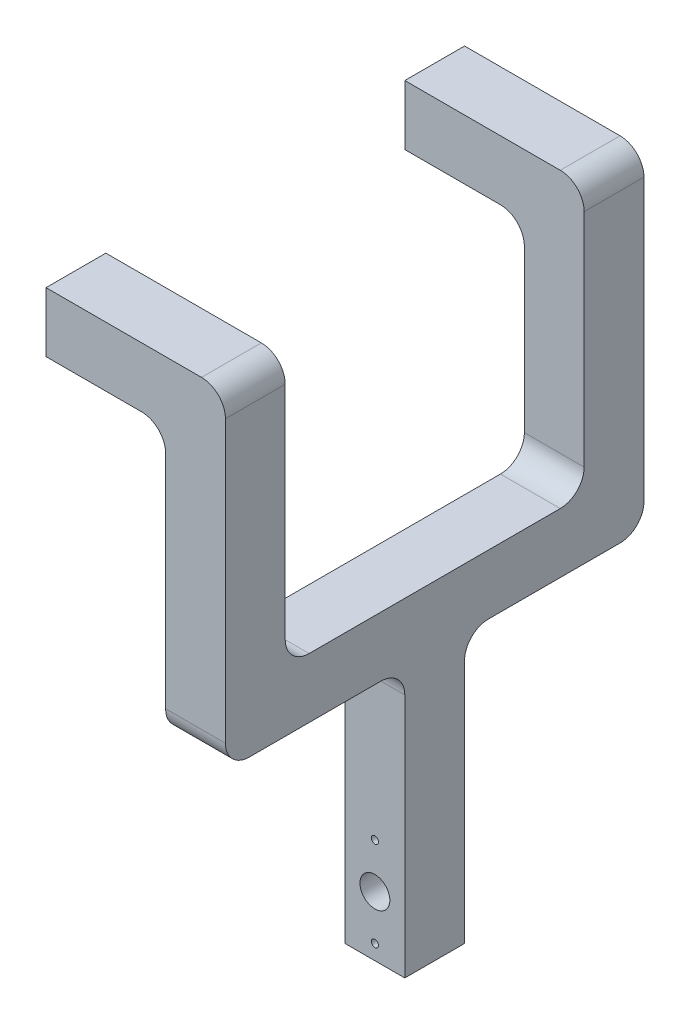
SolidWorks part; units mm, degrees
other "Marquage1"
sketch "Esquisse8" plane through (14, 100, 40) normal (0.0145, 0.0452, 0.9989) x (0.9993, 0.0332, -0.016)
ref_plane "Plan de face" through (0, 0, 0) normal (0, 0, 1) x (1, 0, 0)
ref_plane "Plan de dessus" through (0, 0, 0) normal (0, 1, 0) x (1, 0, 0)
ref_plane "Plan de droite" through (0, 0, 0) normal (1, 0, 0) x (0, 0, -1)
sketch "Esquisse1" plane through (0, 0, 0) normal (0, 0, 1) x (1, 0, 0)
  line L0 (9, 0) -> (9, 10) construction
  line L1 (0, 0) -> (18, 0) construction
  line L2 (0, 0) -> (0, 55) construction
  line L3 (0, 55) -> (18, 55) construction
  line L4 (18, 0) -> (18, 55) construction
  line L5 (9, 10) -> (0, 10) construction
  line L6 (9, 10) -> (9, 17.5) construction
  line L7 (4, 55) -> (14, 55)
  line L8 (4, 55) -> (4, 0)
  line L10 (14, 55) -> (14, 0)
  line L11 (4, 0) -> (14, 0)
  circle A1 centre (9, 10) radius 2.5
  circle A2 centre (9, 17.5) radius 0.5
  circle A4 centre (9, 2.5) radius 0.5
  circle A6 centre (16.5, 10) radius 0.5 [skipped]
  circle A7 centre (1.5, 10) radius 0.5 [skipped]
  point P14 (9, 2.0527)
  point P24 (9, 10)
  dimension "D7" = 5
  dimension "D9" = 1
  dimension "D1" = 18
  dimension "D2" = 55
  dimension "D3" = 10
  dimension "D5" = 10
  dimension "D6" = 4
  dimension "D8" = 7.5
  dimension "D4" = 7.5
  dimension "D10" = 4
extrude "Boss.-Extru.1" add sketch "Esquisse1" along normal blind 10
sketch "Esquisse4" plane through (14, 0, 0) normal (1, 0, 0) x (0, 0, -1)
  line L0 (-30, 55) -> (20, 55)
  line L1 (20, 100) -> (30, 100)
  line L2 (30, 100) -> (30, 45)
  line L3 (30, 45) -> (-40, 45)
  line L4 (-40, 45) -> (-40, 100)
  line L5 (-40, 100) -> (-30, 100)
  line L6 (-30, 100) -> (-30, 55)
  line L8 (20, 55) -> (20, 100)
  line L9 (-5, 55) -> (-5, 0) construction
  line L10 (-10, 55) -> (0, 55) construction
  line L11 (-10, 0) -> (0, 0) construction
  point P5 (-5, 55)
  point P15 (-5, 45)
  dimension "D1" = 70
  dimension "D2" = 10
  dimension "D3" = 10
  dimension "D4" = 100
  dimension "D5" = 100
extrude "Boss.-Extru.2" add sketch "Esquisse4" against normal blind 10
sketch "Esquisse5" plane through (4, 0, 0) normal (-1, 0, 0) x (0, 0, 1)
  line L0 (-20, 100) -> (-20, 55) construction
  line L1 (-30, 100) -> (-20, 100)
  line L2 (-30, 100) -> (-30, 90)
  line L3 (-30, 90) -> (-20, 90)
  line L4 (-20, 100) -> (-20, 90)
  line L5 (40, 100) -> (40, 45) construction
  line L6 (30, 100) -> (40, 100)
  line L7 (30, 100) -> (30, 90)
  line L8 (30, 90) -> (40, 90)
  line L9 (40, 100) -> (40, 90)
  dimension "D1" = 10
extrude "Boss.-Extru.3" add sketch "Esquisse5" along normal blind 20
fillet "Congé1" radius 4 10 edges at (9, 55, -20) (9, 55, 30) (4, 90, -25) (4, 90, 35) (9, 45, -30) (9, 45, 40) (14, 100, -25) (14, 100, 35) (9, 45, 0) (9, 45, 10)
hole_wizard "Dégagement M11" positions "Esquisse6" profile "Esquisse7" hole size "M1" standard "ISO" end condition through all
sketch "Esquisse6" plane through (0, 0, 10) normal (0, 0, 1) x (1, 0, 0)
  point P0 (9, 17.5)
  point P3 (9, 2.5)
sketch "Esquisse7" plane through (9, 17.5, 10) normal (1, 0, 0) x (0, -1, 0)
  line L0 (0, 0) -> (0, 40)
  line L1 (0, 40) -> (0.6, 40)
  line L2 (0.6, 40) -> (0.6, 0)
  line L5 (0.6, 0) -> (0, 0)
  line L11 (0, -6.35) -> (0, 107.95) construction
  dimension "Diamètre du perçage jusqu'au prochain" = 1.2
  dimension "Profondeur du perçage jusqu'au prochain" = 40
equation "\"D3@Esquisse1\"=10"
equation "\"D6@Esquisse1\"=(\"D1@Esquisse1\"-\"D5@Esquisse1\")/2"
equation "\"D8@Esquisse1\"=15/2"
